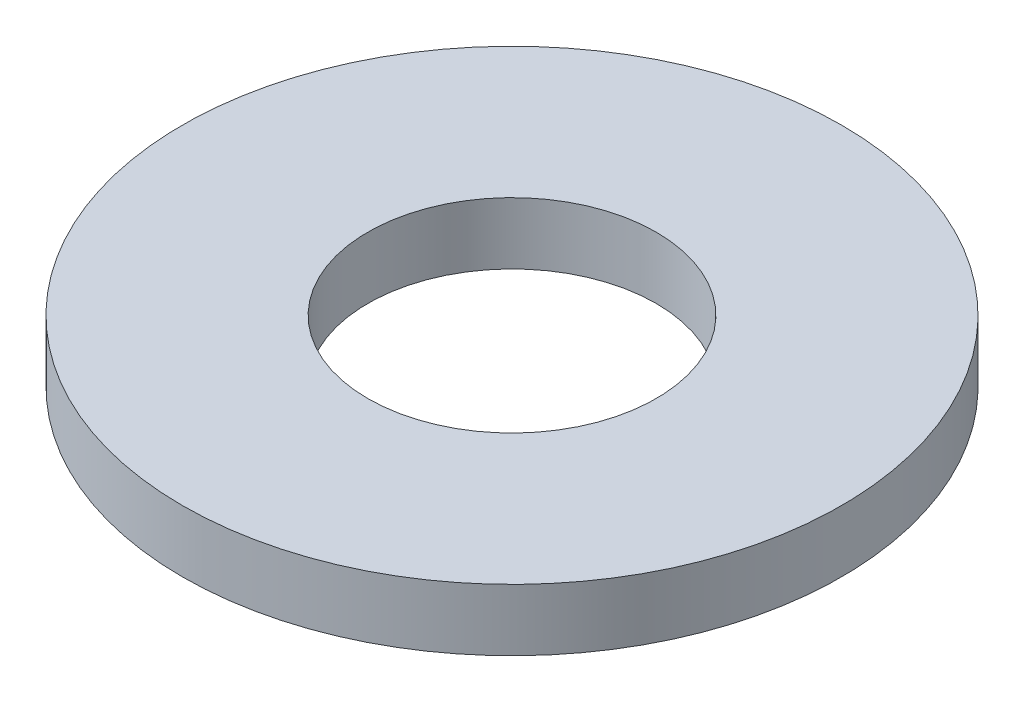
SolidWorks part; units mm, degrees
ref_plane "Front Plane" through (0, 0, 0) normal (0, 0, 1) x (1, 0, 0)
ref_plane "Top Plane" through (0, 0, 0) normal (0, 1, 0) x (1, 0, 0)
ref_plane "Right Plane" through (0, 0, 0) normal (1, 0, 0) x (0, 0, -1)
sketch "Sketch1" plane through (0, 0, 0) normal (0, 1, 0) x (1, 0, 0)
  circle A0 centre (0, 0) radius 8.128
  circle A1 centre (0, 0) radius 3.556
  dimension "D1" = 16.256
  dimension "D2" = 7.112
extrude "Extrude1" add sketch "Sketch1" along normal blind 1.524
